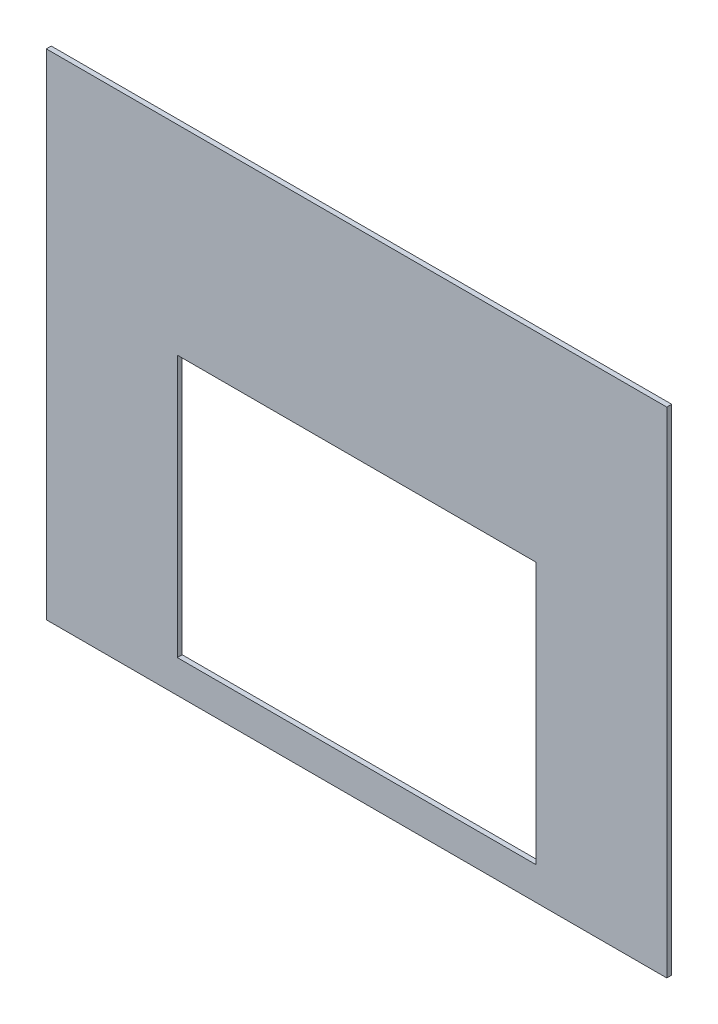
SolidWorks part; units mm, degrees
ref_plane "Front Plane" through (0, 0, 0) normal (0, 0, 1) x (1, 0, 0)
ref_plane "Top Plane" through (0, 0, 0) normal (0, 1, 0) x (1, 0, 0)
ref_plane "Right Plane" through (0, 0, 0) normal (1, 0, 0) x (0, 0, -1)
sketch "Sketch1" plane through (0, 0, 0) normal (0, 0, 1) x (1, 0, 0)
  line L0 (0, 0) -> (-109.5, 0) construction
  line L1 (-189.5, -151) -> (189.5, -151)
  line L2 (-189.5, -151) -> (-189.5, 151)
  line L3 (-189.5, 151) -> (189.5, 151)
  line L4 (189.5, -151) -> (189.5, 151)
  line L5 (-189.5, -151) -> (189.5, 151) construction
  line L6 (-189.5, 151) -> (189.5, -151) construction
  line L7 (-109.5, -151) -> (-109.5, -131) construction
  line L8 (-109.5, -131) -> (-109.5, 29) construction
  line L9 (-109.5, -131) -> (109.5, -131) construction
  line L15 (109.5, -131) -> (-109.5, -131)
  line L16 (109.5, -131) -> (109.5, 29)
  line L17 (109.5, 29) -> (-109.5, 29)
  line L18 (-109.5, -131) -> (-109.5, 29)
  point P0 (0, 0)
extrude "Boss-Extrude1" add sketch "Sketch1" along normal blind 3
